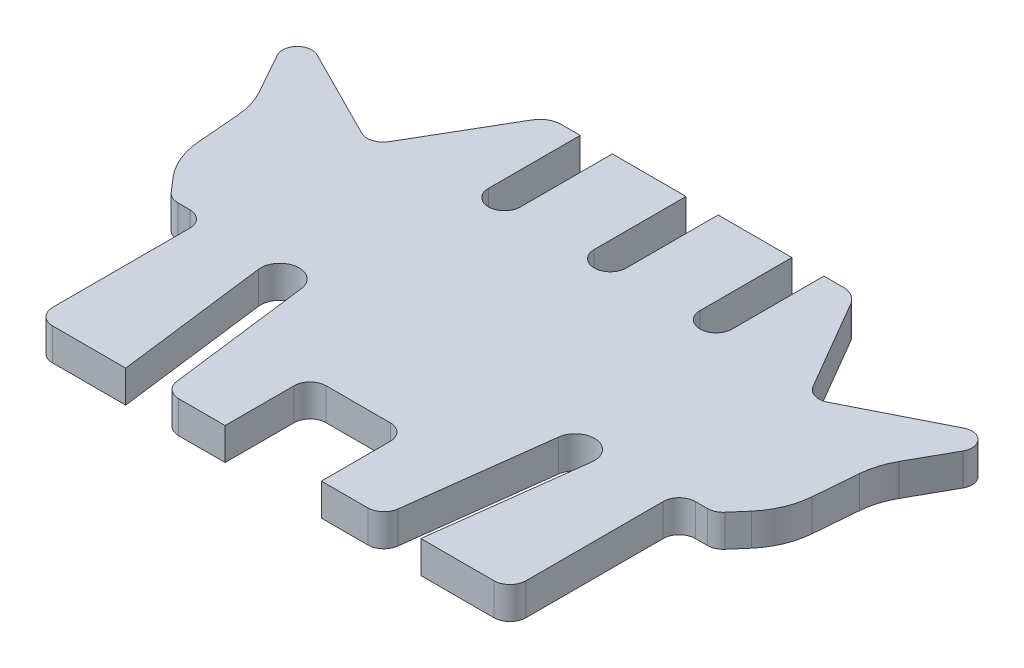
SolidWorks part; units mm, degrees
ref_plane "Front Plane" through (0, 0, 0) normal (0, 0, 1) x (1, 0, 0)
ref_plane "Top Plane" through (0, 0, 0) normal (0, 1, 0) x (1, 0, 0)
ref_plane "Right Plane" through (0, 0, 0) normal (1, 0, 0) x (0, 0, -1)
sketch "Sketch1" plane through (0, 0, 0) normal (0, 1, 0) x (1, 0, 0)
  line L0 (-4.5, 7.94) -> (4.5, 7.94)
  line L1 (4.5, 7.94) -> (4.5, 0)
  line L2 (4.5, 0) -> (10.165, 0)
  line L3 (10.165, 0) -> (12.015, 14.6497)
  line L4 (15.5866, 14.1987) -> (13.7936, 0)
  line L5 (13.7936, 0) -> (22.1245, 0)
  line L6 (22.1245, 15.82) -> (22.1245, 0)
  line L7 (22.1245, 15.82) -> (25.4345, 15.82)
  line L8 (25.4345, 15.82) -> (28.5045, 19.38)
  line L9 (28.5045, 19.38) -> (29.1645, 27.27)
  line L10 (29.1645, 27.27) -> (32.0418, 32.4184)
  line L11 (30.229, 34.31) -> (20.525, 29.4165)
  line L12 (20.525, 29.4165) -> (14.31, 40.08)
  line L13 (14.31, 40.08) -> (11.39, 40.08)
  line L14 (11.39, 40.08) -> (11.39, 31.5)
  line L15 (8.39, 31.5) -> (8.39, 40.08)
  line L16 (8.39, 40.08) -> (1.5, 40.08)
  line L17 (1.5, 40.08) -> (1.5, 31.5)
  line L18 (0, -55) -> (0, 55) construction
  line L19 (-1.5, 40.08) -> (-1.5, 31.5)
  line L20 (-8.39, 40.08) -> (-1.5, 40.08)
  line L21 (-8.39, 31.5) -> (-8.39, 40.08)
  line L22 (-11.39, 40.08) -> (-11.39, 31.5)
  line L23 (-14.31, 40.08) -> (-11.39, 40.08)
  line L24 (-20.525, 29.4165) -> (-14.31, 40.08)
  line L25 (-30.229, 34.31) -> (-20.525, 29.4165)
  line L26 (-29.1645, 27.27) -> (-32.0418, 32.4184)
  line L27 (-28.5045, 19.38) -> (-29.1645, 27.27)
  line L28 (-25.4345, 15.82) -> (-28.5045, 19.38)
  line L29 (-22.1245, 15.82) -> (-25.4345, 15.82)
  line L30 (-22.1245, 15.82) -> (-22.1245, 0)
  line L31 (-13.7936, 0) -> (-22.1245, 0)
  line L32 (-15.5866, 14.1987) -> (-13.7936, 0)
  line L33 (-10.165, 0) -> (-12.015, 14.6497)
  line L34 (-4.5, 0) -> (-10.165, 0)
  line L35 (-4.5, 7.94) -> (-4.5, 0)
  arc A0 (12.015, 14.6497) -> (15.5866, 14.1987) centre (13.8008, 14.4242) cw
  arc A1 (32.0418, 32.4184) -> (30.229, 34.31) centre (30.8459, 33.0867) ccw
  arc A2 (11.39, 31.5) -> (8.39, 31.5) centre (9.89, 31.5) cw
  arc A3 (1.5, 31.5) -> (-1.5, 31.5) centre (0, 31.5) cw
  arc A4 (-11.39, 31.5) -> (-8.39, 31.5) centre (-9.89, 31.5) ccw
  arc A5 (-32.0418, 32.4184) -> (-30.229, 34.31) centre (-30.8459, 33.0867) cw
  arc A6 (-12.015, 14.6497) -> (-15.5866, 14.1987) centre (-13.8008, 14.4242) ccw
  point P29 (0, 30)
  point P30 (14.0263, 16.21)
  point P34 (31.835, 34.0346)
  point P63 (0, 7.94)
  dimension "D2" = 1.8
  dimension "D19" = 29.46
  dimension "D21" = 1.37
  dimension "D23" = 1.5
  dimension "D1" = 40.08
  dimension "D3" = 4.5
  dimension "D4" = 12.015
  dimension "D5" = 17.6245
  dimension "D6" = 7.94
  dimension "D7" = 10.165
  dimension "D8" = 16.21
  dimension "D9" = 3.31
  dimension "D10" = 6.38
  dimension "D11" = 3.56
  dimension "D12" = 11.45
  dimension "D13" = 7.04
  dimension "D14" = 18.49
  dimension "D15" = 15.82
  dimension "D16" = 6.89
  dimension "D17" = 14.31
  dimension "D18" = 10.08
  dimension "D20" = 20.525
  dimension "D22" = 31.835
extrude "Boss-Extrude1" add sketch "Sketch1" along normal blind 3
fillet "Fillet1" radius 1.5 12 edges at (25.4345, 1.5, -15.82) (22.1245, 1.5, -15.82) (-22.1245, 1.5, 0) (22.1245, 1.5, 0) (-4.5, 1.5, -7.94) (4.5, 1.5, -7.94) (20.525, 1.5, -29.4165) (-20.525, 1.5, -29.4165) (-22.1245, 1.5, -15.82) (-25.4345, 1.5, -15.82) (10.165, 1.5, 0) (-10.165, 1.5, 0)
fillet "Fillet2" radius 7 4 edges at (-28.5045, 1.5, -19.38) (28.5045, 1.5, -19.38) (29.1645, 1.5, -27.27) (-29.1645, 1.5, -27.27)
fillet "Fillet3" radius 2 2 edges at (-14.31, 1.5, -40.08) (14.31, 1.5, -40.08)
